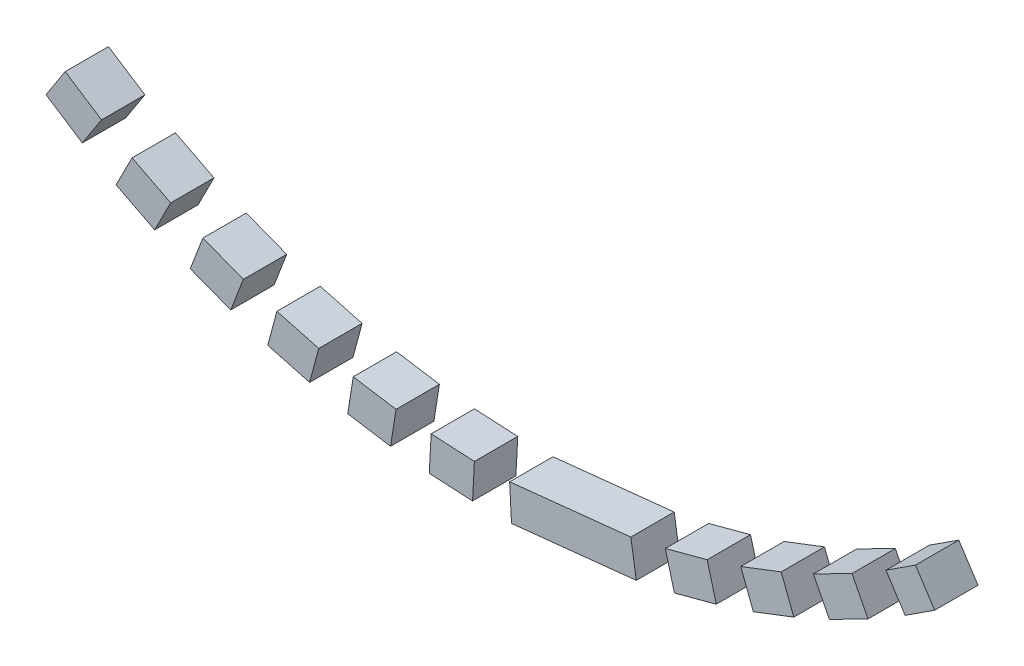
SolidWorks part; units mm, degrees
ref_plane "Front Plane" through (0, 0, 0) normal (0, 0, 1) x (1, 0, 0)
ref_plane "Top Plane" through (0, 0, 0) normal (0, 1, 0) x (1, 0, 0)
ref_plane "Right Plane" through (0, 0, 0) normal (1, 0, 0) x (0, 0, -1)
sketch "Contact Datums" plane through (0, 0, 0) normal (0, 0, 1) x (1, 0, 0)
  line L0 (0, 0) -> (0, -28.35) construction
  line L1 (0, 0) -> (-15.4405, -23.7763) construction
  line L2 (0, 0) -> (-15.4405, -23.7763) construction
  line L3 (0, 0) -> (-12.8706, -25.26) construction
  line L4 (0, 0) -> (15.4405, -23.7763) construction
  line L5 (0, 0) -> (0, 28.35) construction
  circle A0 centre (0, 0) radius 28.35 construction
  circle A1 centre (-15.4405, -23.7763) radius 0.5 construction
  circle A2 centre (-12.8706, -25.26) radius 0.5 construction
  circle A3 centre (-10.1597, -26.467) radius 0.5 construction
  circle A4 centre (-7.3375, -27.384) radius 0.5 construction
  circle A5 centre (-4.4349, -28.001) radius 0.5 construction
  circle A6 centre (-1.4837, -28.3111) radius 0.5 construction
  circle A7 centre (1.4837, -28.3111) radius 0.5 construction
  circle A8 centre (4.4349, -28.001) radius 0.5 construction
  circle A9 centre (7.3375, -27.384) radius 0.5 construction
  circle A10 centre (10.1597, -26.467) radius 0.5 construction
  circle A11 centre (12.8706, -25.26) radius 0.5 construction
  circle A12 centre (15.4405, -23.7763) radius 0.5 construction
  dimension "D1" = 56.7
  dimension "D3" = 1
  dimension "D2" = 33
  dimension "D5" = 6
  dimension "D4" = 12
sketch "Sketch3" plane through (0, 0, 0) normal (0, 0, 1) x (1, 0, 0)
  line L0 (-16.4655, -23.8857) -> (-15.1236, -24.7572)
  line L1 (-16.4655, -23.8857) -> (-15.7574, -22.7955)
  line L2 (-15.1236, -24.7572) -> (-14.4156, -23.6669)
  line L3 (-15.7574, -22.7955) -> (-14.4156, -23.6669)
  line L4 (-16.4655, -23.8857) -> (-14.4156, -23.6669) construction
  line L5 (-15.1236, -24.7572) -> (-15.7574, -22.7955) construction
  line L6 (-15.4405, -23.7763) -> (-14.7696, -24.212) construction
  line L7 (-13.8785, -25.476) -> (-12.4529, -26.2024)
  line L8 (-12.4529, -26.2024) -> (-11.8627, -25.0441)
  line L9 (-13.2883, -24.3177) -> (-11.8627, -25.0441)
  line L10 (-13.8785, -25.476) -> (-13.2883, -24.3177)
  line L11 (-11.1395, -26.7871) -> (-9.6458, -27.3605)
  line L12 (-9.6458, -27.3605) -> (-9.1799, -26.1469)
  line L13 (-10.6737, -25.5735) -> (-9.1799, -26.1469)
  line L14 (-11.1395, -26.7871) -> (-10.6737, -25.5735)
  line L15 (-8.2785, -27.8048) -> (-6.733, -28.2189)
  line L16 (-6.733, -28.2189) -> (-6.3965, -26.9632)
  line L17 (-7.942, -26.5491) -> (-6.3965, -26.9632)
  line L18 (-8.2785, -27.8048) -> (-7.942, -26.5491)
  line L19 (-5.3268, -28.5178) -> (-3.7464, -28.7681)
  line L20 (-3.7464, -28.7681) -> (-3.5431, -27.4841)
  line L21 (-5.1234, -27.2338) -> (-3.5431, -27.4841)
  line L22 (-5.3268, -28.5178) -> (-5.1234, -27.2338)
  line L23 (-2.3166, -28.9184) -> (-0.7188, -29.0021)
  line L24 (-0.7188, -29.0021) -> (-0.6508, -27.7039)
  line L25 (-2.2486, -27.6202) -> (-0.6508, -27.7039)
  line L26 (-2.3166, -28.9184) -> (-2.2486, -27.6202)
  line L27 (0.7188, -29.0021) -> (2.3166, -28.9184) construction
  line L28 (2.3166, -28.9184) -> (2.2486, -27.6202) construction
  line L29 (0.6508, -27.7039) -> (2.2486, -27.6202) construction
  line L30 (0.7188, -29.0021) -> (0.6508, -27.7039)
  line L31 (3.7464, -28.7681) -> (5.3268, -28.5178) construction
  line L32 (5.3268, -28.5178) -> (5.1234, -27.2338)
  line L33 (3.5431, -27.4841) -> (5.1234, -27.2338) construction
  line L34 (3.7464, -28.7681) -> (3.5431, -27.4841) construction
  line L35 (6.733, -28.2189) -> (8.2785, -27.8048)
  line L36 (8.2785, -27.8048) -> (7.942, -26.5491)
  line L37 (6.3965, -26.9632) -> (7.942, -26.5491)
  line L38 (6.733, -28.2189) -> (6.3965, -26.9632)
  line L39 (9.6458, -27.3605) -> (11.1395, -26.7871)
  line L40 (11.1395, -26.7871) -> (10.6737, -25.5735)
  line L41 (9.1799, -26.1469) -> (10.6737, -25.5735)
  line L42 (9.6458, -27.3605) -> (9.1799, -26.1469)
  line L43 (12.4529, -26.2024) -> (13.8785, -25.476)
  line L44 (13.8785, -25.476) -> (13.2883, -24.3177)
  line L45 (11.8627, -25.0441) -> (13.2883, -24.3177)
  line L46 (12.4529, -26.2024) -> (11.8627, -25.0441)
  line L51 (15.2494, -24.6755) -> (16.3397, -23.9674)
  line L52 (15.2494, -24.6755) -> (14.5414, -23.5852)
  line L53 (16.3397, -23.9674) -> (15.6316, -22.8772)
  line L54 (11.8627, -25.0441) -> (13.8785, -25.476) construction
  line L55 (13.2883, -24.3177) -> (12.4529, -26.2024) construction
  line L56 (12.8706, -25.26) -> (13.5834, -24.8968) construction
  line L57 (14.5414, -23.5852) -> (15.6316, -22.8772)
  line L58 (15.2494, -24.6755) -> (15.6316, -22.8772) construction
  line L59 (16.3397, -23.9674) -> (14.5414, -23.5852) construction
  line L60 (15.4405, -23.7763) -> (15.9857, -23.4223) construction
  line L61 (5.1234, -27.2338) -> (0.6508, -27.7039)
  line L62 (5.3268, -28.5178) -> (0.7188, -29.0021)
  circle A0 centre (0, 0) radius 28.35 construction
  point P1 (-15.4405, -23.7763)
  point P11 (15.4405, -23.7763)
  point P57 (0, 0)
  dimension "D1" = 1.6
  dimension "D2" = 1.3
  dimension "D3" = 11
extrude "Contacts" add sketch "Sketch3" along normal blind 1.6
sketch "Lens mount mech-references" plane through (0, 0, 0) normal (0, 0, 1) x (1, 0, 0)
  circle A0 centre (0, 0) radius 29.775 construction
  circle A1 centre (0, 0) radius 26.275 construction
  circle A3 centre (0, 0) radius 27.675 construction
  circle A4 centre (0, 0) radius 29.025 construction
  dimension "D1" = 52.55
  dimension "D2" = 59.55
  dimension "D3" = 1.4
  dimension "D4" = 0.75
